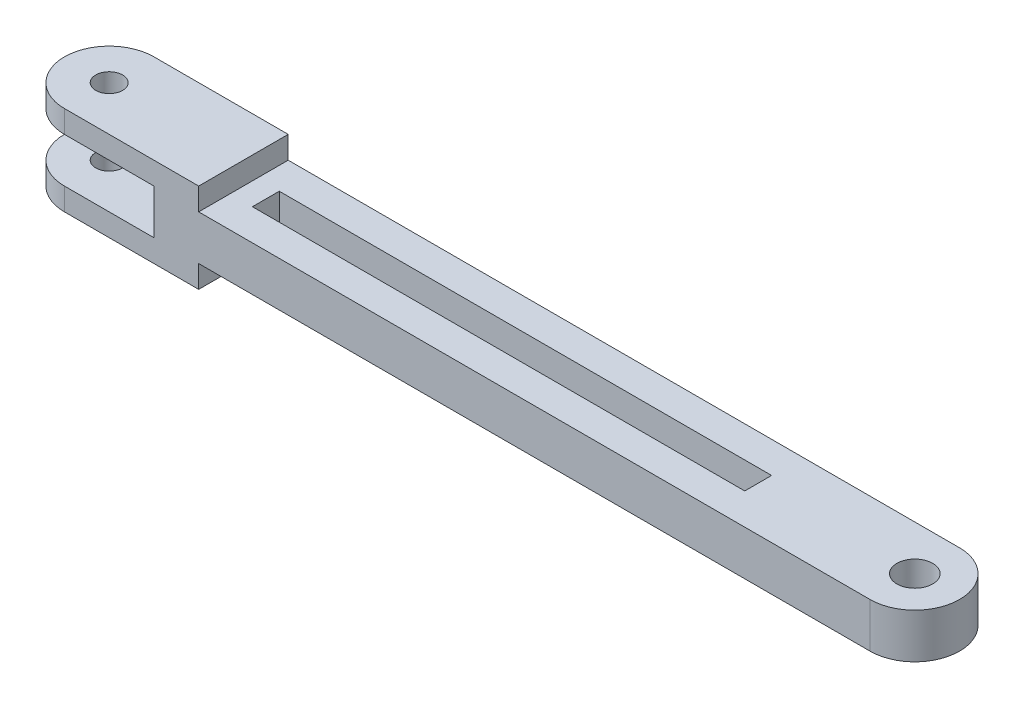
SolidWorks part; units mm, degrees
ref_plane "Alzado" through (0, 0, 0) normal (0, 0, 1) x (1, 0, 0)
ref_plane "Planta" through (0, 0, 0) normal (0, 1, 0) x (1, 0, 0)
ref_plane "Vista lateral" through (0, 0, 0) normal (1, 0, 0) x (0, 0, -1)
sketch "Croquis1" plane through (0, 0, 0) normal (0, 0, 1) x (1, 0, 0)
  line L1 (0, 0) -> (105, 0)
  line L2 (0, 0) -> (0, 2.5)
  line L3 (0, 10) -> (105, 10)
  line L5 (105, 2.5) -> (105, 0)
  line L7 (0, 7.5) -> (0, 10)
  line L9 (0, 7.5) -> (15, 7.5)
  line L12 (105, 7.5) -> (105, 10)
  line L13 (105, 7.5) -> (105, 2.5)
  line L14 (0, 2.5) -> (15, 2.5)
  line L15 (15, 7.5) -> (15, 2.5)
  dimension "D1" = 15
  dimension "D2" = 10
  dimension "D3" = 105
extrude "Saliente-Extruir1" add sketch "Croquis1" along normal blind 10
sketch "Croquis2" plane through (0, 10, 0) normal (0, 1, 0) x (1, 0, 0)
  line L0 (0, -5) -> (105, -5) construction
  line L1 (0, -10) -> (0, 0) construction
  line L3 (-4.0319, 0) -> (5, 0)
  line L4 (-4.0319, 0) -> (-4.0319, -10)
  line L5 (-4.0319, -10) -> (5, -10)
  line L6 (105, -10) -> (105, 0) construction
  line L8 (22.5, -6.5) -> (77.5, -6.5)
  line L9 (22.5, -6.5) -> (22.5, -3.5)
  line L10 (22.5, -3.5) -> (77.5, -3.5)
  line L11 (77.5, -6.5) -> (77.5, -3.5)
  circle A0 centre (5, -5) radius 1.5
  arc A2 (5, 0) -> (5, -10) centre (5, -5) ccw
  point P8 (52.5, -5)
  dimension "D1" = 3
  dimension "D2" = 5
  dimension "D3" = 3
  dimension "D4" = 55
  dimension "D5" = 30
  dimension "D6" = 1.5
extrude "Cortar-Extruir1" cut sketch "Croquis2" against normal blind 10
sketch "Croquis3" plane through (0, 10, 0) normal (0, 1, 0) x (1, 0, 0)
  line L0 (105, -5) -> (87.1029, -5) construction
  line L1 (105, -10) -> (105, 0) construction
  line L2 (105, 0) -> (5, 0) construction
  line L3 (90, 0) -> (105, 0)
  line L4 (90, 0) -> (90, -2.5)
  line L5 (90, -2.5) -> (105, -2.5)
  line L6 (105, 0) -> (105, -2.5)
  line L7 (105, -10) -> (105, -7.5)
  line L8 (90, -7.5) -> (105, -7.5)
  line L9 (90, -10) -> (90, -7.5)
  line L10 (90, -10) -> (105, -10)
  dimension "D1" = 15
  dimension "D2" = 2.5
extrude "Cortar-Extruir2" cut sketch "Croquis3" against normal blind 10
sketch "Croquis4" plane through (0, 0, 7.5) normal (0, 0, 1) x (1, 0, 0)
  line L0 (105, 0) -> (105, 10) construction
  line L1 (100, 10) -> (171.1124, 10)
  line L2 (171.1124, 10) -> (171.1124, 0)
  line L3 (171.1124, 0) -> (100, 0)
  line L4 (90, 0) -> (90, 10) construction
  circle A0 centre (100, 5) radius 1.5
  arc A1 (100, 0) -> (100, 10) centre (100, 5) ccw
  dimension "D2" = 10
  dimension "D3" = 3
  dimension "D1" = 5
  dimension "D4" = 81.1124
extrude "Cortar-Extruir3" cut sketch "Croquis4" against normal blind 10
sketch "Croquis8" plane through (0, 0, 7.5) normal (0, 0, 1) x (1, 0, 0)
  line L3 (90, 0) -> (100, 0)
  line L4 (100, 10) -> (90, 10)
  line L5 (90, 10) -> (90, 0)
  line L6 (90, 0) -> (100, 0)
  line L7 (100, 10) -> (90, 10)
  line L8 (90, 10) -> (90, 0)
  arc A1 (100, 0) -> (100, 10) centre (100, 5) ccw
  arc A2 (100, 0) -> (100, 10) centre (100, 5) ccw
  dimension "D1" = 0
extrude "Cortar-Extruir5" cut sketch "Croquis8" against normal blind 10
ref_plane "Plano1" through (0, 5, 0) normal (0, -1, 0) x (-1, 0, 0)
sketch "Croquis9" plane through (0, 5, 0) normal (0, -1, 0) x (-1, 0, 0)
  line L0 (-90, 0) -> (-90, -10) construction
  line L1 (-90, -10) -> (-95, -10)
  line L2 (-90, -10) -> (-90, 0)
  line L3 (-90, 0) -> (-95, 0)
  line L4 (-100, -5) -> (-100, 12.5399) construction
  circle A0 centre (-95, -5) radius 2
  arc A1 (-95, 0) -> (-95, -10) centre (-95, -5) ccw
  dimension "D2" = 4
  dimension "D1" = 100
extrude "Saliente-Extruir2" add sketch "Croquis9" along normal mid plane 5
sketch "Croquis10" plane through (0, 0, 0) normal (0, 0, -1) x (-1, 0, 0)
  line L0 (-100, 5) -> (-117.0786, 5) construction
  line L2 (-90, 7.5) -> (-20, 7.5)
  line L3 (-90, 7.5) -> (-90, 23.6446)
  line L4 (-90, 23.6446) -> (-20, 23.6446)
  line L5 (-20, 7.5) -> (-20, 23.6446)
  line L6 (-100, 7.5) -> (-100, 2.5) construction
  line L7 (-20, 2.5) -> (-20, -13.6446)
  line L8 (-90, -13.6446) -> (-20, -13.6446)
  line L10 (-90, 2.5) -> (-90, -13.6446)
  line L11 (-90, 2.5) -> (-20, 2.5)
  dimension "D1" = 70
extrude "Cortar-Extruir6" cut sketch "Croquis10" against normal blind 10
